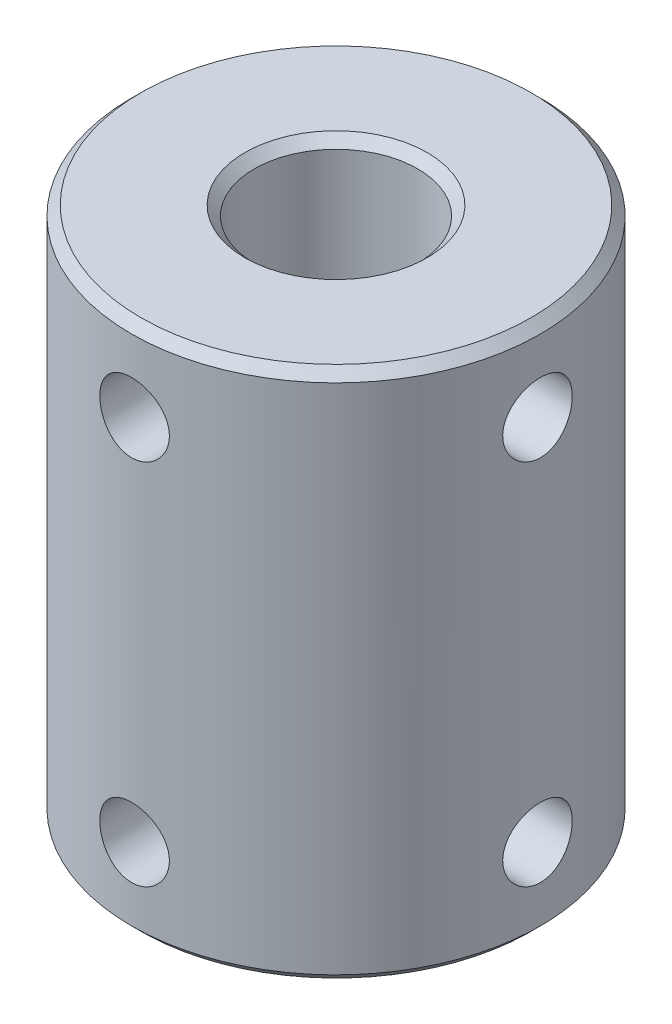
SolidWorks part; units mm, degrees
material "3.0205 (EN-AW 1200)"
ref_plane "Alzado" through (0, 0, 0) normal (0, 0, 1) x (1, 0, 0)
ref_plane "Planta" through (0, 0, 0) normal (0, 1, 0) x (1, 0, 0)
ref_plane "Vista lateral" through (0, 0, 0) normal (1, 0, 0) x (0, 0, -1)
ref_plane "Plano1" through (0, 0, 0) normal (0, 0, -1) x (-1, 0, 0)
sketch "Croquis1" plane through (0, 0, 0) normal (0, 0, -1) x (-1, 0, 0)
  line L0 (-10, -13) -> (0, -13)
  line L1 (0, -13) -> (0, 13)
  line L2 (0, 13) -> (-10, 13)
  line L3 (-10, 13) -> (-10, -13)
  line L4 (0, -13) -> (0, 13) construction
revolve "Revolución1" add sketch "Croquis1" angle 360 about L4
hole_wizard "Taladro roscado M8x1.01" positions "Croquis3" profile "Croquis2" tap size "M8x1.0" standard "Ansi Metric"
sketch "Croquis3" plane through (0, 13, 0) normal (0, 1, 0) x (1, 0, 0)
  point P0 (0, 0)
sketch "Croquis2" plane through (0, 13, 0) normal (1, 0, 0) x (0, 0, 1)
  line L0 (0, 0) -> (0, 26)
  line L1 (0, 26) -> (2.5, 26)
  line L3 (2.5, 26) -> (2.5, 18.5)
  line L4 (2.5, 18.5) -> (4, 18.5)
  line L5 (4, 18.5) -> (4, 0)
  line L7 (4, 0) -> (0, 0)
  line L11 (0, -6.35) -> (0, 107.95) construction
  dimension "Diámetro de perforador para roscar hasta el siguiente" = 5
  dimension "Profundidad de perforador para roscar hasta el siguiente" = 26
  dimension "Diámetro mayor de rosca" = 8
  dimension "Profundidad de rosca" = 18.5
hole_wizard "Diámetro de taladro Ø3.4 (3.4)1" positions "Croquis3D1" profile "Croquis4" hole size "Ø3.4" standard "Ansi Metric"
sketch3d "Croquis3D1"
  point P0 (0, -9, 10)
sketch "Croquis4" plane through (0, -9, 10) normal (1, 0, 0) x (0, -1, 0)
  line L0 (0, 0) -> (0, 7.5)
  line L1 (0, 7.5) -> (1.7, 7.5)
  line L2 (1.7, 7.5) -> (1.7, 0)
  line L5 (1.7, 0) -> (0, 0)
  line L11 (0, -6.35) -> (0, 107.95) construction
  dimension "Diámetro de taladro hasta el siguiente" = 3.4
  dimension "Profundidad de taladro hasta el siguiente" = 7.5
hole_wizard "Diámetro de taladro Ø3.4 (3.4)2" positions "Croquis3D2" profile "Croquis5" hole size "Ø3.4" standard "Ansi Metric"
sketch3d "Croquis3D2"
  point P0 (10, -9, 0)
sketch "Croquis5" plane through (10, -9, 0) normal (0, 1, 0) x (0, 0, -1)
  line L0 (0, 0) -> (0, 7.5)
  line L1 (0, 7.5) -> (1.7, 7.5)
  line L2 (1.7, 7.5) -> (1.7, 0)
  line L5 (1.7, 0) -> (0, 0)
  line L11 (0, -6.35) -> (0, 107.95) construction
  dimension "Diámetro de taladro hasta el siguiente" = 3.4
  dimension "Profundidad de taladro hasta el siguiente" = 7.5
hole_wizard "Diámetro de taladro Ø3.4 (3.4)3" positions "Croquis3D3" profile "Croquis6" hole size "Ø3.4" standard "Ansi Metric"
sketch3d "Croquis3D3"
  point P0 (0, 9, 10)
sketch "Croquis6" plane through (0, 9, 10) normal (1, 0, 0) x (0, -1, 0)
  line L0 (0, 0) -> (0, 6)
  line L1 (0, 6) -> (1.7, 6)
  line L2 (1.7, 6) -> (1.7, 0)
  line L5 (1.7, 0) -> (0, 0)
  line L11 (0, -6.35) -> (0, 107.95) construction
  dimension "Diámetro de taladro hasta el siguiente" = 3.4
  dimension "Profundidad de taladro hasta el siguiente" = 6
hole_wizard "Diámetro de taladro Ø3.4 (3.4)4" positions "Croquis3D4" profile "Croquis7" hole size "Ø3.4" standard "Ansi Metric"
sketch3d "Croquis3D4"
  point P0 (10, 9, 0)
sketch "Croquis7" plane through (10, 9, 0) normal (0, 1, 0) x (0, 0, -1)
  line L0 (0, 0) -> (0, 6)
  line L1 (0, 6) -> (1.7, 6)
  line L2 (1.7, 6) -> (1.7, 0)
  line L5 (1.7, 0) -> (0, 0)
  line L11 (0, -6.35) -> (0, 107.95) construction
  dimension "Diámetro de taladro hasta el siguiente" = 3.4
  dimension "Profundidad de taladro hasta el siguiente" = 6
chamfer "Chaflán1" distance 0.46 angle 45 4 edges at (0, 13, 10) (0, 13, 4) (0, -13, 10) (0, -13, 2.5)
